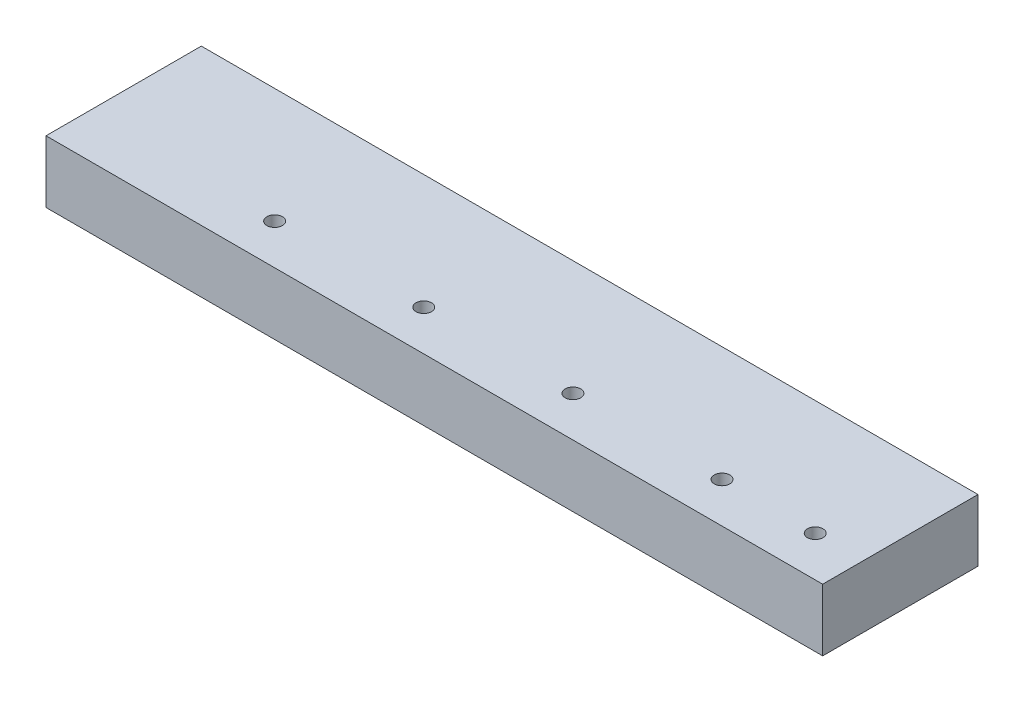
SolidWorks part; units mm, degrees
ref_plane "Спереди" through (0, 0, 0) normal (0, 0, 1) x (1, 0, 0)
ref_plane "Сверху" through (0, 0, 0) normal (0, 1, 0) x (1, 0, 0)
ref_plane "Справа" through (0, 0, 0) normal (1, 0, 0) x (0, 0, -1)
sketch "Эскиз1" plane through (0, 0, 0) normal (0, 0, 1) x (1, 0, 0)
  line L1 (-57.3521, -13.3505) -> (67.6479, -13.3505)
  line L2 (-57.3521, -13.3505) -> (-57.3521, -23.3505)
  line L3 (-57.3521, -23.3505) -> (67.6479, -23.3505)
  line L4 (67.6479, -13.3505) -> (67.6479, -23.3505)
  dimension "D1" = 10
  dimension "D2" = 125
extrude "Бобышка-Вытянуть1" add sketch "Эскиз1" along normal blind 25
hole_wizard "Отверстие обработанное метчиком M3x0.52" positions "Эскиз5" profile "Эскиз6" tap size "M3x0.5" standard "Ansi (метрические)"
sketch "Эскиз5" plane through (0, 0, 0) normal (0, 0, -1) x (-1, 0, 0)
  line L0 (-67.6479, -23.3505) -> (-67.6479, -13.3505) construction
  line L1 (57.3521, -13.3505) -> (57.3521, -23.3505) construction
  line L2 (-67.6479, -18.3505) -> (57.3521, -18.3505) construction
  point P0 (-62.6479, -18.3505)
  point P1 (52.3521, -18.3505)
  dimension "D1" = 5
  dimension "D2" = 5
sketch "Эскиз6" plane through (62.6479, -18.3505, 0) normal (1, 0, 0) x (0, 1, 0)
  line L0 (0, 0) -> (0, 13.2511)
  line L1 (0, 13.2511) -> (1.25, 12.5)
  line L2 (1.25, 12.5) -> (1.25, 0)
  line L5 (1.25, 0) -> (0, 0)
  line L10 (0, 13.2511) -> (-1.25, 12.5) construction
  line L11 (0, -6.35) -> (0, 107.95) construction
  dimension "Диаметр сверла" = 2.5
  dimension "Глубина сверла" = 12.5
  dimension "Угол заточки сверла" = 118
cosmetic thread "Отверстие резьбы1" parameters "D1"=10, "D2"=3
cosmetic thread "Отверстие резьбы2" parameters "D1"=10, "D2"=3
hole_wizard "Отверстие обработанное метчиком M3x0.51" positions "Эскиз8" profile "Эскиз7" tap size "M3x0.5" standard "Ansi (метрические)" end condition through all
sketch "Эскиз8" plane through (0, -13.3505, 0) normal (0, 1, 0) x (-1, 0, 0)
  line L0 (57.3521, 25) -> (57.3521, 0) construction
  line L1 (-67.6479, 0) -> (57.3521, 0) construction
  point P0 (-44.9479, 18.5)
  point P1 (-20.9479, 18.5)
  point P3 (3.0521, 18.5)
  point P5 (27.0521, 18.5)
  point P14 (-59.9479, 18.5)
  dimension "D1" = 30.3
  dimension "D2" = 24
  dimension "D3" = 24
  dimension "D4" = 24
  dimension "D5" = 18.5
  dimension "D6" = 15
sketch "Эскиз7" plane through (44.9479, -13.3505, 18.5) normal (1, 0, 0) x (0, 0, 1)
  line L0 (0, 0) -> (0, 10)
  line L1 (0, 10) -> (1.25, 10)
  line L2 (1.25, 10) -> (1.25, 0)
  line L5 (1.25, 0) -> (0, 0)
  line L11 (0, -6.35) -> (0, 107.95) construction
  dimension "Диаметр проходного сверла" = 2.5
  dimension "Глубина проходного сверла" = 10
cosmetic thread "Отверстие резьбы3" parameters "D2"=3
cosmetic thread "Отверстие резьбы4" parameters "D2"=3
cosmetic thread "Отверстие резьбы5" parameters "D2"=3
cosmetic thread "Отверстие резьбы6" parameters "D2"=3
cosmetic thread "Отверстие резьбы7" parameters "D2"=3
